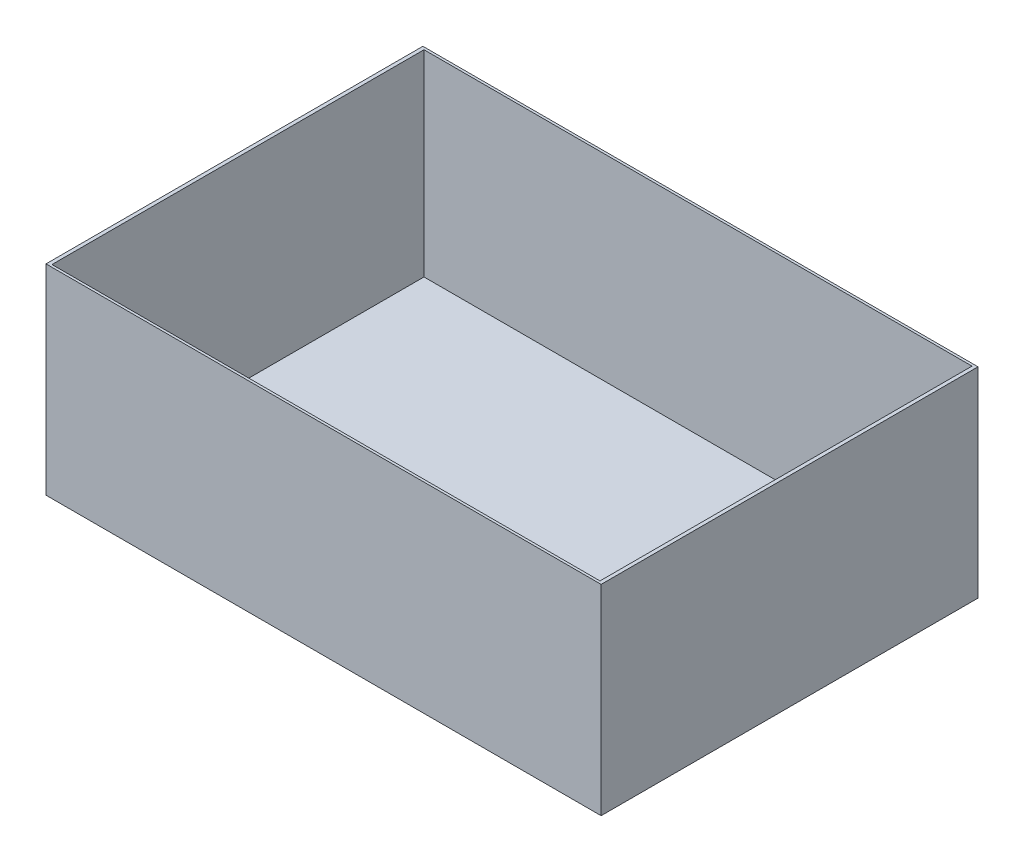
SolidWorks part; units mm, degrees
material "5052-H32"
ref_plane "Front Plane" through (0, 0, 0) normal (0, 0, 1) x (1, 0, 0)
ref_plane "Top Plane" through (0, 0, 0) normal (0, 1, 0) x (1, 0, 0)
ref_plane "Right Plane" through (0, 0, 0) normal (1, 0, 0) x (0, 0, -1)
sketch "Sketch1" plane through (0, 0, 0) normal (0, 1, 0) x (1, 0, 0)
  line L1 (-249.22, 169.19) -> (249.22, 169.19)
  line L2 (-249.22, 169.19) -> (-249.22, -169.19)
  line L3 (-249.22, -169.19) -> (249.22, -169.19)
  line L4 (249.22, 169.19) -> (249.22, -169.19)
  line L5 (-249.22, 169.19) -> (249.22, -169.19) construction
  line L6 (-249.22, -169.19) -> (249.22, 169.19) construction
  point P0 (0, 0)
  dimension "D1" = 338.38
  dimension "D2" = 498.44
extrude "Boss-Extrude1" add sketch "Sketch1" along normal blind 3.2
sketch "Sketch2" plane through (0, 3.2, 0) normal (0, 1, 0) x (1, 0, 0)
  line L1 (-249.22, -169.19) -> (249.22, -169.19)
  line L2 (-249.22, -169.19) -> (-249.22, 169.19)
  line L3 (-249.22, 169.19) -> (249.22, 169.19)
  line L4 (249.22, -169.19) -> (249.22, 169.19)
  line L5 (-249.22, -169.19) -> (249.22, 169.19) construction
  line L6 (-249.22, 169.19) -> (249.22, -169.19) construction
  line L7 (-246.02, -167.0176) -> (246.02, -167.0176)
  line L8 (-246.02, -167.0176) -> (-246.02, 167.0176)
  line L9 (-246.02, 167.0176) -> (246.02, 167.0176)
  line L10 (246.02, -167.0176) -> (246.02, 167.0176)
  line L11 (-246.02, -167.0176) -> (246.02, 167.0176) construction
  line L12 (-246.02, 167.0176) -> (246.02, -167.0176) construction
  point P0 (0, 0)
  point P5 (0, 0)
  dimension "D1" = 3.2
extrude "Boss-Extrude2" add sketch "Sketch2" along normal blind 176.7
